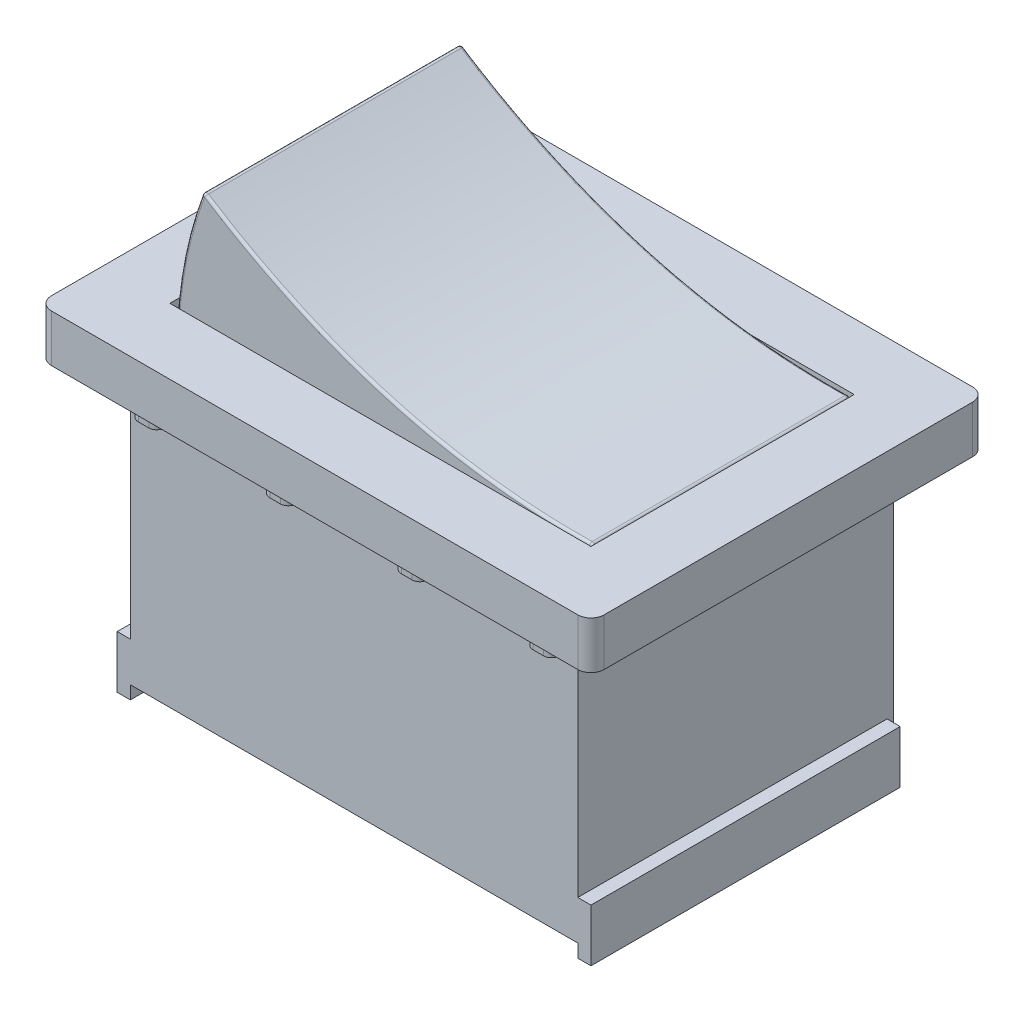
SolidWorks part; units mm, degrees
ref_plane "Alzado" through (0, 0, 0) normal (0, 0, 1) x (1, 0, 0)
ref_plane "Planta" through (0, 0, 0) normal (0, 1, 0) x (1, 0, 0)
ref_plane "Vista lateral" through (0, 0, 0) normal (1, 0, 0) x (0, 0, -1)
sketch "Croquis1" plane through (0, 0, 0) normal (0, 1, 0) x (1, 0, 0)
  line L1 (-10, -7.5) -> (10, -7.5)
  line L2 (-10.5, -7) -> (-10.5, 7)
  line L3 (-10, 7.5) -> (10, 7.5)
  line L4 (10.5, -7) -> (10.5, 7)
  line L5 (-10.5, -7.5) -> (10.5, 7.5) construction
  line L6 (-10.5, 7.5) -> (10.5, -7.5) construction
  arc A0 (-10, -7.5) -> (-10.5, -7) centre (-10, -7) cw
  arc A1 (10, -7.5) -> (10.5, -7) centre (10, -7) ccw
  arc A2 (10, 7.5) -> (10.5, 7) centre (10, 7) cw
  arc A3 (-10.5, 7) -> (-10, 7.5) centre (-10, 7) cw
  point P0 (0, 0)
  dimension "D3" = 0.5
  dimension "D1" = 21
  dimension "D2" = 15
extrude "Saliente-Extruir1" add sketch "Croquis1" along normal blind 1.8
sketch "Croquis2" plane through (0, 1.8, 0) normal (0, 1, 0) x (1, 0, 0)
  line L1 (-8, -5) -> (8, -5)
  line L2 (-8, -5) -> (-8, 5)
  line L3 (-8, 5) -> (8, 5)
  line L4 (8, -5) -> (8, 5)
  line L5 (-8, -5) -> (8, 5) construction
  line L6 (-8, 5) -> (8, -5) construction
  point P0 (0, 0)
  dimension "D1" = 10
  dimension "D2" = 16
extrude "Cortar-Extruir1" cut sketch "Croquis2" against normal blind 1.5
sketch "Croquis3" plane through (0, 0, 0) normal (0, 0, 1) x (1, 0, 0)
  line L0 (-7.875, 0.3) -> (8.0884, 0.3) construction
  line L6 (-0.5781, 0.3) -> (0, 0) construction
  line L8 (8.0469, 1.7936) -> (8.0884, 0.3)
  line L11 (0, 0) -> (0.5781, 0.3) construction
  line L13 (-10, 0) -> (10, 0) construction
  line L14 (8.0884, 0.3) -> (-7.875, 0.3)
  arc A0 (-6.834, 6) -> (-7.875, 0.3) centre (8.25, 0.3) ccw
  spline S0 degree 3 poles (-6.834, 6) (-2.2825, 3.0467) (2.6778, 1.6446) (8.0469, 1.7936) knots 0 0 0 0 0.987562 0.987562 0.987562 0.987562
  point P0 (0, 0)
  dimension "D3" = 32.25
  dimension "D2" = 0.3
  dimension "D4" = 6
extrude "Saliente-Extruir3" add sketch "Croquis3" along normal blind 4.9 and the other way blind 4.9
sketch "Croquis4" plane through (0, 1.8, 0) normal (0, 1, 0) x (1, 0, 0)
  line L0 (-8, -5) -> (8, -5) construction
  line L1 (8, 5) -> (7.95, 5)
  line L2 (8, 5) -> (8, -5)
  line L3 (8, -5) -> (7.95, -5)
  line L4 (7.95, 5) -> (7.95, -5)
  dimension "D1" = 0.05
extrude "Cortar-Extruir2" cut sketch "Croquis4" against normal blind 1.7
fillet "Redondeo1" radius 0.1 1 edges at (7.95, 1.7911, 0)
fillet "Redondeo2" radius 0.1 9 edges at (7.95, 0.9944, -4.9) (7.92, 1.7603, -4.9) (7.95, 0.9944, 4.9) (7.92, 1.7603, 4.9) (-7.6126, 3.1971, -4.9) (-6.834, 6, 0) (-7.6126, 3.1971, 4.9)
sketch "Croquis5" plane through (0, 0, 0) normal (0, -1, 0) x (1, 0, 0)
  line L1 (-8.5, -6) -> (8.5, -6)
  line L2 (-8.5, -6) -> (-8.5, 6)
  line L3 (-8.5, 6) -> (8.5, 6)
  line L4 (8.5, -6) -> (8.5, 6)
  line L5 (-8.5, -6) -> (8.5, 6) construction
  line L6 (-8.5, 6) -> (8.5, -6) construction
  point P0 (0, 0)
  dimension "D1" = 12
  dimension "D2" = 17
extrude "Saliente-Extruir4" add sketch "Croquis5" along normal blind 10.5
sketch "Croquis6" plane through (0, 0, 0) normal (0, -1, 0) x (1, 0, 0)
  line L0 (0, 7.5) -> (0, -7.5) construction
  line L1 (-10, 7.5) -> (10, 7.5) construction
  line L2 (10, -7.5) -> (-10, -7.5) construction
  line L3 (8.5, 6) -> (-8.5, 6) construction
  line L4 (2, 6) -> (3, 6)
  line L5 (2, 6) -> (2, 6.2)
  line L6 (2.3, 6.5) -> (2.7, 6.5)
  line L7 (3, 6) -> (3, 6.2)
  line L8 (7.3, 6.5) -> (7.7, 6.5)
  line L9 (8, 6) -> (8, 6.2)
  line L10 (7, 6) -> (7, 6.2)
  line L11 (7.3, 6.5) -> (7.7, 6.5)
  line L12 (8, 6) -> (8, 6.2)
  line L13 (7, 6) -> (7, 6.2)
  line L14 (-2.7, 6.5) -> (-2.3, 6.5)
  line L15 (-2, 6) -> (-2, 6.2)
  line L16 (-3, 6) -> (-3, 6.2)
  line L17 (-7.7, 6.5) -> (-7.3, 6.5)
  line L18 (-7, 6) -> (-7, 6.2)
  line L19 (-8, 6) -> (-8, 6.2)
  line L20 (-8.5, 0) -> (8.5, 0) construction
  line L21 (-8.5, 6) -> (-8.5, -6) construction
  line L22 (8.5, -6) -> (8.5, 6) construction
  line L23 (-8, -6) -> (-8, -6.2)
  line L24 (-7, -6) -> (-7, -6.2)
  line L25 (-7.7, -6.5) -> (-7.3, -6.5)
  line L26 (-3, -6) -> (-3, -6.2)
  line L27 (-2, -6) -> (-2, -6.2)
  line L28 (-2.7, -6.5) -> (-2.3, -6.5)
  line L29 (7, -6) -> (7, -6.2)
  line L30 (8, -6) -> (8, -6.2)
  line L31 (7.3, -6.5) -> (7.7, -6.5)
  line L32 (7, -6) -> (7, -6.2)
  line L33 (8, -6) -> (8, -6.2)
  line L34 (7.3, -6.5) -> (7.7, -6.5)
  line L35 (3, -6) -> (3, -6.2)
  line L36 (2.3, -6.5) -> (2.7, -6.5)
  line L37 (2, -6) -> (2, -6.2)
  line L38 (2, -6) -> (3, -6)
  arc A0 (2, 6.2) -> (2.3, 6.5) centre (2.3, 6.2) cw
  arc A1 (2.7, 6.5) -> (3, 6.2) centre (2.7, 6.2) cw
  arc A2 (7, 6.2) -> (7.3, 6.5) centre (7.3, 6.2) cw
  arc A3 (7, 6.2) -> (7.3, 6.5) centre (7.3, 6.2) cw
  arc A4 (7.7, 6.5) -> (8, 6.2) centre (7.7, 6.2) cw
  arc A5 (-3, 6.2) -> (-2.7, 6.5) centre (-2.7, 6.2) cw
  arc A6 (-2.3, 6.5) -> (-2, 6.2) centre (-2.3, 6.2) cw
  arc A7 (-8, 6.2) -> (-7.7, 6.5) centre (-7.7, 6.2) cw
  arc A8 (-7.3, 6.5) -> (-7, 6.2) centre (-7.3, 6.2) cw
  arc A9 (-7.3, -6.5) -> (-7, -6.2) centre (-7.3, -6.2) ccw
  arc A10 (-8, -6.2) -> (-7.7, -6.5) centre (-7.7, -6.2) ccw
  arc A11 (-2.3, -6.5) -> (-2, -6.2) centre (-2.3, -6.2) ccw
  arc A12 (-3, -6.2) -> (-2.7, -6.5) centre (-2.7, -6.2) ccw
  arc A13 (7.7, -6.5) -> (8, -6.2) centre (7.7, -6.2) ccw
  arc A14 (7, -6.2) -> (7.3, -6.5) centre (7.3, -6.2) ccw
  arc A15 (7, -6.2) -> (7.3, -6.5) centre (7.3, -6.2) ccw
  arc A16 (2.7, -6.5) -> (3, -6.2) centre (2.7, -6.2) ccw
  arc A17 (2, -6.2) -> (2.3, -6.5) centre (2.3, -6.2) ccw
  point P14 (2, 6.5)
  point P17 (3, 6.5)
  point P85 (3, -6.5)
  point P86 (2, -6.5)
  line M36 (-8.5, 6) -> (8.5, 6)
  line M38 (8.5, -6) -> (-8.5, -6)
  dimension "D3" = 0.3
  dimension "D1" = 1
  dimension "D2" = 2
  dimension "D4" = 0.5
  dimension "D7" = 3
  dimension "D5" = 2
  dimension "D6" = 2
extrude "Saliente-Extruir5" add sketch "Croquis6" along normal blind 1.2 contours A8 L17 A7 L19 L18 M36 | A6 L14 A5 L16 L15 M36 | A1 L6 A0 L5 L7 M36 | A4 L8 A2 L10 L9 M36 | L37 A17 L36 A16 L35 M38 | L29 A14 L31 A13 L30 M38 | L26 A12 L28 A11 L27 M38 | L23 A10 L25 A9 L24 M38
sketch "Croquis7" plane through (8.5, 0, 0) normal (1, 0, 0) x (0, 0, -1)
  line L0 (-6, -10.5) -> (6, -10.5) construction
  line L1 (-6, -10.5) -> (-6, 0) construction
  line L2 (-6, -9) -> (5.75, -9)
  line L3 (-6, -9) -> (-6, -11)
  line L4 (-6, -11) -> (5.75, -11)
  line L5 (5.75, -9) -> (5.75, -11)
  dimension "D1" = 1.5
  dimension "D2" = 0.5
extrude "Saliente-Extruir6" add sketch "Croquis7" along normal blind 0.5
sketch "Croquis8" plane through (-8.5, 0, 0) normal (-1, 0, 0) x (0, 0, 1)
  line L0 (-6, -10.5) -> (6, -10.5) construction
  line L1 (-6, -10.5) -> (-6, 0) construction
  line L2 (-6, -9) -> (6, -9)
  line L3 (-6, -9) -> (-6, -11)
  line L4 (-6, -11) -> (6, -11)
  line L5 (6, -9) -> (6, -11)
  dimension "D1" = 1.5
extrude "Saliente-Extruir7" add sketch "Croquis8" along normal blind 0.5
